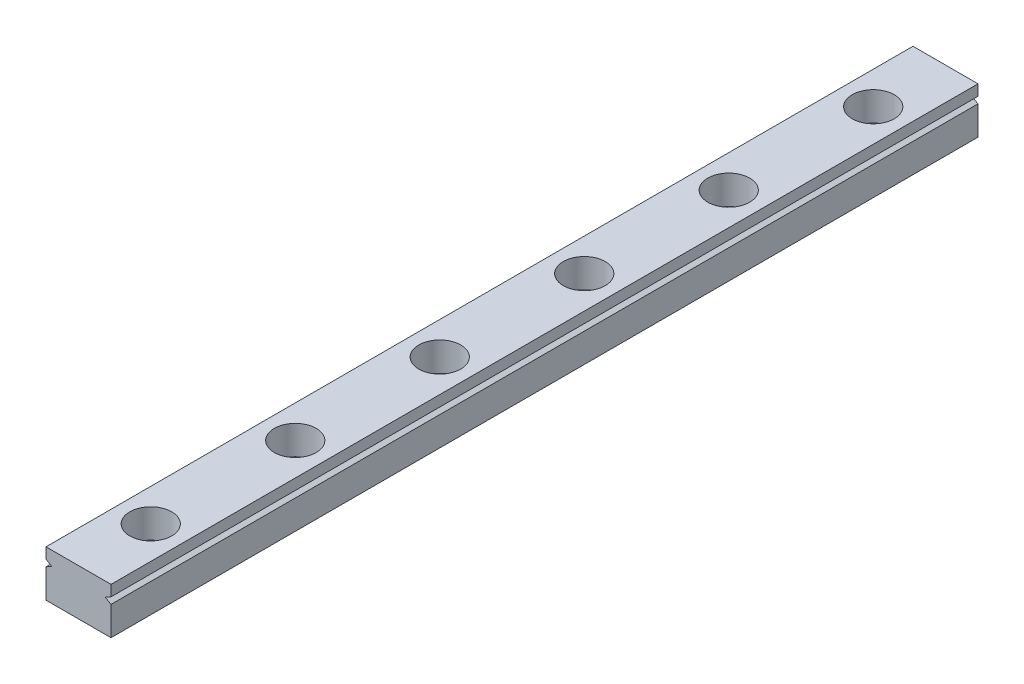
SolidWorks part; units mm, degrees
ref_plane "Front Plane" through (0, 0, 0) normal (0, 0, 1) x (1, 0, 0)
ref_plane "Top Plane" through (0, 0, 0) normal (0, 1, 0) x (1, 0, 0)
ref_plane "Right Plane" through (0, 0, 0) normal (1, 0, 0) x (0, 0, -1)
sketch "Sketch1" plane through (0, 0, 0) normal (0, 0, 1) x (1, 0, 0)
  line L0 (9, 6.4) -> (9, 4.9)
  line L1 (0, 0) -> (9, 0)
  line L2 (0, 0) -> (0, 6.4) construction
  line L3 (0, 6.4) -> (9, 6.4)
  line L4 (9, 0) -> (9, 6.4) construction
  line L5 (9, 4.9) -> (8.2, 4.45)
  line L6 (8.2, 4.45) -> (9, 4)
  line L7 (9, 4) -> (9, 0)
  line L8 (0, 6.4) -> (0, 4.9)
  line L9 (0, 4.9) -> (0.8, 4.45)
  line L10 (0.8, 4.45) -> (0, 4)
  line L11 (0, 4) -> (0, 0)
  line L12 (4.5, 6.4) -> (4.5, 0) construction
  line L13 (9, 4.9) -> (9, 4) construction
  line L14 (9, 4.45) -> (0, 4.45) construction
  dimension "D1" = 9
  dimension "D2" = 6.4
  dimension "D3" = 1.5
  dimension "D4" = 4
  dimension "D5" = 0.8
extrude "Boss-Extrude1" add sketch "Sketch1" along normal blind 120
sketch "Sketch2" plane through (0, 6.4, 0) normal (0, 1, 0) x (1, 0, 0)
  line L0 (4.5, -120) -> (4.5, 0) construction
  line L1 (9, -120) -> (0, -120) construction
  line L2 (9, 0) -> (0, 0) construction
  circle A0 centre (4.5, -110) radius 2.9
  circle A1 centre (4.5, -90) radius 2.9
  circle A2 centre (4.5, -70) radius 2.9
  circle A3 centre (4.5, -50) radius 2.9
  circle A4 centre (4.5, -30) radius 2.9
  circle A5 centre (4.5, -10) radius 2.9
  circle A6 centre (4.5, 10) radius 2.9
  dimension "D1" = 5.8
  dimension "D2" = 10
  dimension "D4" = 20
  dimension "D3" = 7
extrude "Cut-Extrude1" cut sketch "Sketch2" against normal blind 4
sketch "Sketch3" plane through (0, 2.4, 0) normal (0, 1, 0) x (1, 0, 0)
  circle A0 centre (4.5, -110) radius 1.7
  circle A1 centre (4.5, -110) radius 2.9 construction
  circle A2 centre (4.5, -90) radius 1.7
  circle A3 centre (4.5, -70) radius 1.7
  circle A4 centre (4.5, -50) radius 1.7
  circle A5 centre (4.5, -30) radius 1.7
  circle A6 centre (4.5, -10) radius 1.7
  circle A7 centre (4.5, 10) radius 1.7
  dimension "D1" = 3.4
  dimension "D2" = 7
extrude "Cut-Extrude2" cut sketch "Sketch3" against normal through all
